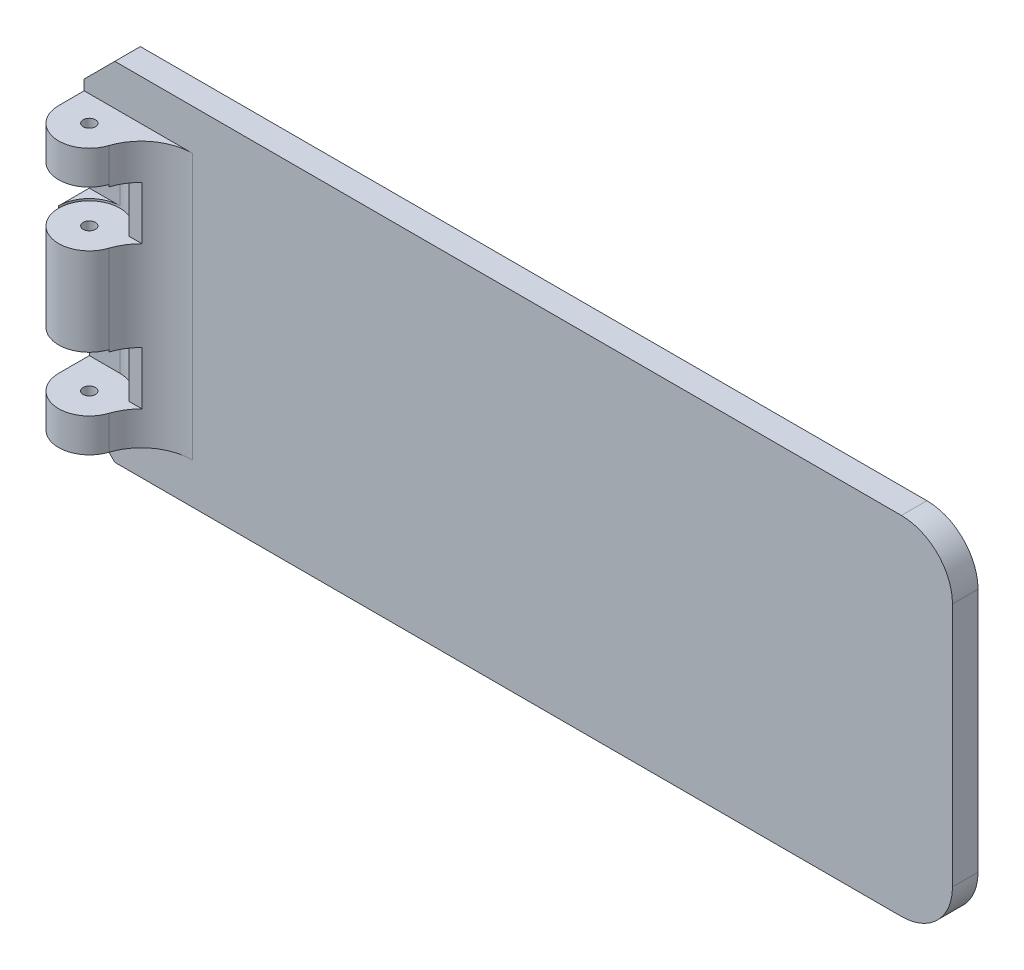
SolidWorks part; units mm, degrees
ref_plane "Front Plane" through (0, 0, 0) normal (0, 0, 1) x (1, 0, 0)
ref_plane "Top Plane" through (0, 0, 0) normal (0, 1, 0) x (1, 0, 0)
ref_plane "Right Plane" through (0, 0, 0) normal (1, 0, 0) x (0, 0, -1)
sketch "Sketch1" plane through (0, 0, 0) normal (0, 1, 0) x (1, 0, 0)
  line L0 (3, 0) -> (3, -11.9691) construction
  line L1 (0, 0) -> (85, 0)
  line L2 (0, 0) -> (0, -2.5)
  line L3 (0, -2.5) -> (85, -2.5)
  line L4 (85, 0) -> (85, -2.5)
  line L5 (0, -5) -> (0, -2.5)
  line L6 (0, -2.5) -> (3, -2.5)
  line L7 (3, -2.5) -> (0, -5)
  circle A0 centre (3, -5) radius 0.6
  circle A1 centre (3, -5) radius 3
  dimension "D3" = 3
  dimension "D1" = 85
  dimension "D2" = 2.5
  dimension "D4" = 5
extrude "Boss-Extrude1" add sketch "Sketch1" along normal blind 34 contours L1 L0 A1 L3 L4 | L0 L1 L2 L3 A1 | A1 L3 L5 | L0 L7 A1 A0 | L3 L0 A0 A1 | L6 A1 L7 | L0 A1 L6 | A1 L0 L3
fillet "Fillet1" radius 5 1 edges at (4.6583, 17, 2.5)
sketch "Sketch2" plane through (0, 0, 0) normal (0, 0, -1) x (-1, 0, 0)
  line L0 (0, 17) -> (-85, 17) construction
  line L3 (0, 34) -> (0, 0) construction
  line L4 (-85, 34) -> (-85, 0) construction
  line L5 (0, 10) -> (-43.2696, 10) construction
  line L6 (0, 24) -> (-43.2696, 24) construction
  dimension "D1" = 7
  dimension "D2" = 7
ref_plane "Plane1" through (0, 10, 0) normal (0, 1, 0) x (1, 0, 0)
ref_plane "Plane2" through (0, 24, 0) normal (0, 1, 0) x (1, 0, 0)
sketch "Sketch3" plane through (0, 24, 0) normal (0, 1, 0) x (1, 0, 0)
  circle A0 centre (3, -5) radius 3
extrude "Cut-Extrude1" cut sketch "Sketch3" against normal blind 2.7 and the other way blind 2.7
sketch "Sketch5" plane through (0, 24, 0) normal (0, 1, 0) x (1, 0, 0)
  line L0 (3, -2) -> (-2.0945, -2)
  line L1 (-2.0945, -2) -> (-2.0945, -6.1355)
  line L2 (-2.0945, -6.1355) -> (2.7202, -6.1355)
  line L3 (2.7202, -6.1355) -> (3, -2)
  arc A0 (5.8498, -5.9375) -> (0, -5) centre (3, -5) ccw construction
extrude "Cut-Extrude2" cut sketch "Sketch5" against normal blind 2.5 and the other way blind 2.5
sketch "Sketch6" plane through (0, 10, 0) normal (0, 1, 0) x (1, 0, 0)
  line L0 (3, -2) -> (0, -2)
  line L1 (0, 0) -> (0, -5) construction
  line L2 (0, -2) -> (0, -5)
  circle A0 centre (3, -5) radius 3
extrude "Cut-Extrude3" cut sketch "Sketch6" against normal blind 2.7 and the other way blind 2.7 contours A0 | A0 L0 L2
sketch "Sketch7" plane through (0, 34, 0) normal (0, 1, 0) x (1, 0, 0)
  line L0 (10.5993, -2.5) -> (85, -2.5) construction
  line L1 (14.8947, -2.5) -> (-5.5535, -2.5)
  line L2 (14.8947, -2.5) -> (14.8947, -12.2075)
  line L3 (14.8947, -12.2075) -> (-5.5535, -12.2075)
  line L4 (-5.5535, -2.5) -> (-5.5535, -12.2075)
extrude "Cut-Extrude4" cut sketch "Sketch7" against normal blind 4
sketch "Sketch8" plane through (0, 0, 0) normal (0, -1, 0) x (1, 0, 0)
  line L0 (10.5993, 2.5) -> (85, 2.5) construction
  line L1 (14.4693, 2.5) -> (-7.0314, 2.5)
  line L2 (14.4693, 2.5) -> (14.4693, 10.5053)
  line L3 (14.4693, 10.5053) -> (-7.0314, 10.5053)
  line L4 (-7.0314, 2.5) -> (-7.0314, 10.5053)
extrude "Cut-Extrude5" cut sketch "Sketch8" against normal blind 4
chamfer "Chamfer1" distance 3 angle 45 2 edges at (0, 34, 1.25) (0, 0, 1.25)
fillet "Fillet2" radius 5 2 edges at (85, 0, 1.25) (85, 34, 1.25)
ref_plane "Plane3" through (0, 0, 5.9375) normal (0, 0, 1) x (1, 0, 0)
sketch "Sketch9" plane through (0, 0, 5.9375) normal (0, 0, 1) x (1, 0, 0)
  line L0 (5.8498, 7.3) -> (0, 7.3) construction
  line L1 (3.4675, 7.3) -> (8.9635, 7.3)
  line L2 (3.4675, 7.3) -> (3.4675, 12.5)
  line L3 (3.4675, 12.5) -> (8.9635, 12.5)
  line L4 (8.9635, 7.3) -> (8.9635, 12.5)
  line L5 (5.8498, 21.3) -> (0, 21.3) construction
  line L6 (3, 21.3) -> (8.5264, 21.3)
  line L7 (3, 21.3) -> (3, 26.5)
  line L8 (3, 26.5) -> (8.5264, 26.5)
  line L9 (8.5264, 21.3) -> (8.5264, 26.5)
  line L10 (6, 21.3) -> (0, 21.3) construction
extrude "Cut-Extrude6" cut sketch "Sketch9" against normal blind 2
